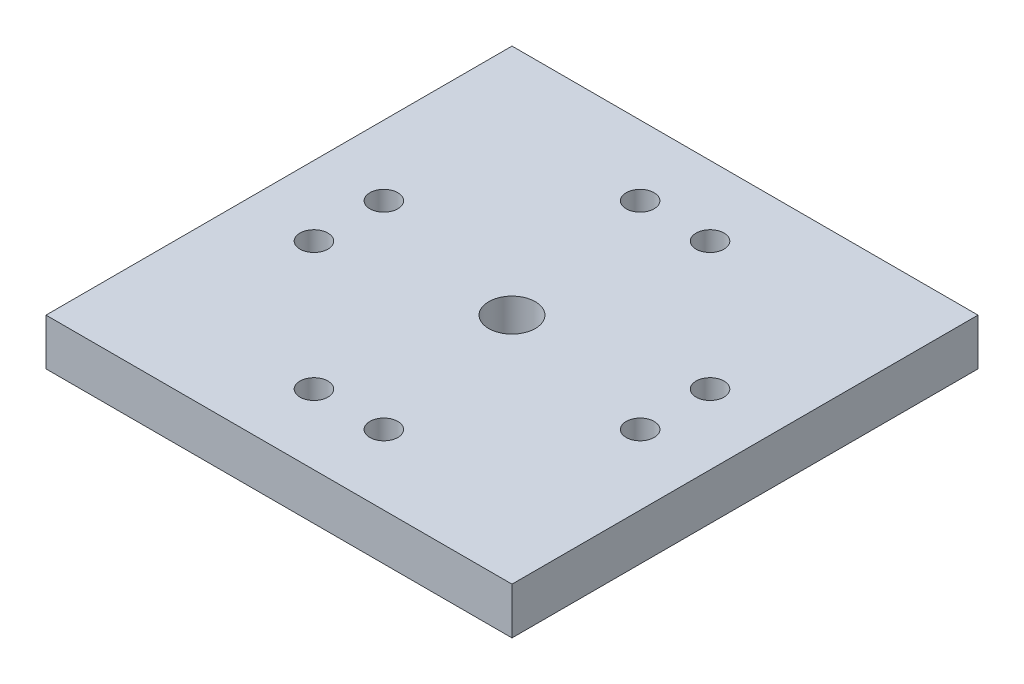
SolidWorks part; units mm, degrees
ref_plane "Front Plane" through (0, 0, 0) normal (0, 0, 1) x (1, 0, 0)
ref_plane "Top Plane" through (0, 0, 0) normal (0, 1, 0) x (1, 0, 0)
ref_plane "Right Plane" through (0, 0, 0) normal (1, 0, 0) x (0, 0, -1)
sketch "Sketch1" plane through (0, 0, 0) normal (0, 1, 0) x (1, 0, 0)
  line L0 (0, 0) -> (0, 50000) construction
  line L1 (50, -50) -> (-50, -50)
  line L2 (50, -50) -> (50, 50)
  line L3 (50, 50) -> (-50, 50)
  line L4 (-50, -50) -> (-50, 50)
  line L5 (50, -50) -> (-50, 50) construction
  line L6 (50, 50) -> (-50, -50) construction
  line L7 (-3.1231, 0) -> (-50003.1231, 0) construction
  line L9 (7.5, 35) -> (-7.5, 35) construction
  line L10 (7.5, 35) -> (7.5, 60) construction
  line L11 (7.5, 60) -> (-7.5, 60) construction
  line L12 (-7.5, 35) -> (-7.5, 60) construction
  circle A0 centre (0, 0) radius 30 construction
  circle A1 centre (0, 0) radius 5
  circle A2 centre (-7.5, 35) radius 3
  circle A3 centre (7.5, 35) radius 3
  circle A4 centre (35, 7.5) radius 3
  circle A5 centre (35, -7.5) radius 3
  circle A6 centre (7.5, -35) radius 3
  circle A7 centre (-7.5, -35) radius 3
  circle A8 centre (-35, -7.5) radius 3
  circle A9 centre (-35, 7.5) radius 3
  point P0 (0, 0)
  point P34 (0, 0)
  dimension "D1" = 60
  dimension "D4" = 10
  dimension "D9" = 6
  dimension "D10" = 6
  dimension "D2" = 100
  dimension "D3" = 100
  dimension "D5" = 15
  dimension "D6" = 7.5
  dimension "D7" = 7.5
  dimension "D8" = 10
  dimension "D11" = 4
extrude "Boss-Extrude1" add sketch "Sketch1" along normal blind 10
